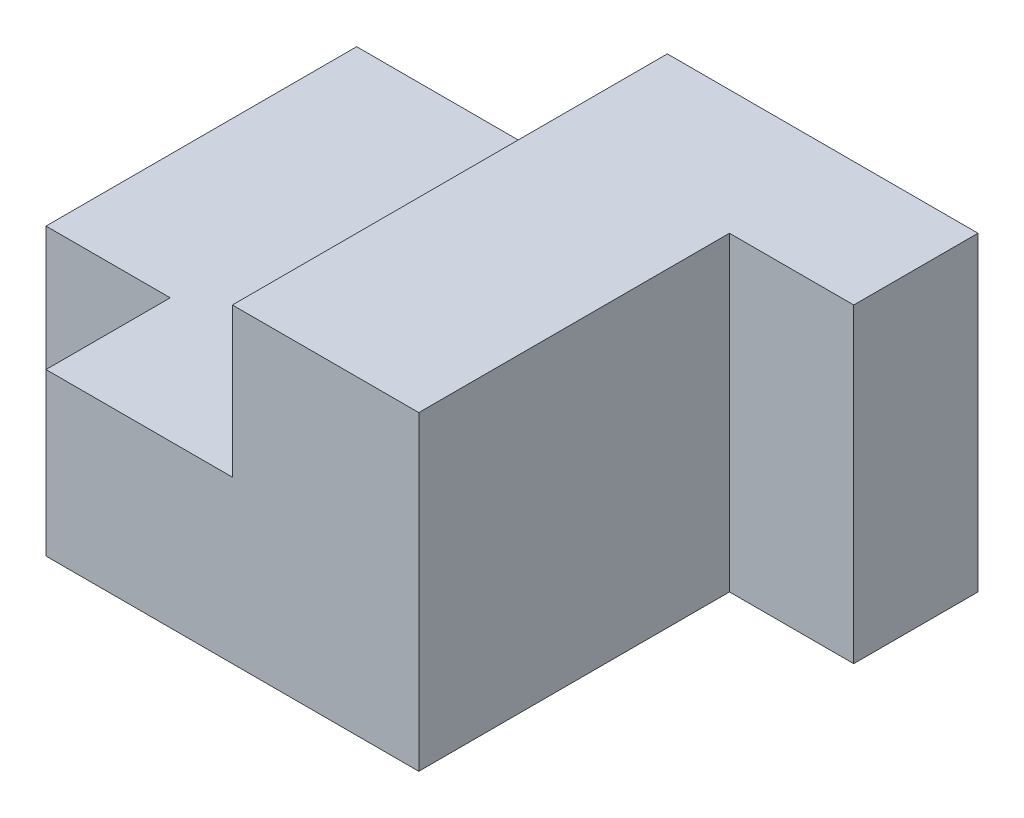
SolidWorks part; units mm, degrees
ref_plane "Front Plane" through (0, 0, 0) normal (0, 0, 1) x (1, 0, 0)
ref_plane "Top Plane" through (0, 0, 0) normal (0, 1, 0) x (1, 0, 0)
ref_plane "Right Plane" through (0, 0, 0) normal (1, 0, 0) x (0, 0, -1)
sketch "Sketch1" plane through (0, 0, 0) normal (0, 1, 0) x (1, 0, 0)
  line L0 (27.4257, 33.1188) -> (27.4257, 13.1188)
  line L1 (27.4257, 13.1188) -> (7.4257, 13.1188)
  line L2 (7.4257, 13.1188) -> (7.4257, -36.8812)
  line L3 (7.4257, -36.8812) -> (-22.5743, -36.8812)
  line L4 (-22.5743, -36.8812) -> (-22.5743, 33.1188)
  line L5 (-22.5743, 33.1188) -> (27.4257, 33.1188)
  dimension "D1" = 20
  dimension "D2" = 50
  dimension "D3" = 30
  dimension "D4" = 50
extrude "Boss-Extrude1" add sketch "Sketch1" along normal blind 50
sketch "Sketch2" plane through (0, 0, 0) normal (0, 1, 0) x (1, 0, 0)
  line L0 (-22.5743, 33.1188) -> (-72.5743, 33.1188)
  line L1 (-72.5743, 33.1188) -> (-72.5743, -16.8812)
  line L2 (-72.5743, -16.8812) -> (-52.5743, -16.8812)
  line L3 (-52.5743, -16.8812) -> (-52.5743, -36.8812)
  line L4 (-22.5743, -36.8812) -> (-52.5743, -36.8812)
  line L11 (27.4257, 33.1188) -> (-22.5743, 33.1188)
  line L12 (-22.5743, 33.1188) -> (-22.5743, -36.8812)
  line L13 (-22.5743, -36.8812) -> (7.4257, -36.8812)
  line L14 (7.4257, -36.8812) -> (7.4257, 13.1188)
  line L15 (7.4257, 13.1188) -> (27.4257, 13.1188)
  line L16 (27.4257, 13.1188) -> (27.4257, 33.1188)
  line L18 (-22.5743, 33.1188) -> (-22.5743, -36.8812)
  dimension "D1" = 50
  dimension "D2" = 50
  dimension "D3" = 30
  dimension "D4" = 0
extrude "Boss-Extrude2" add sketch "Sketch2" along normal blind 26
